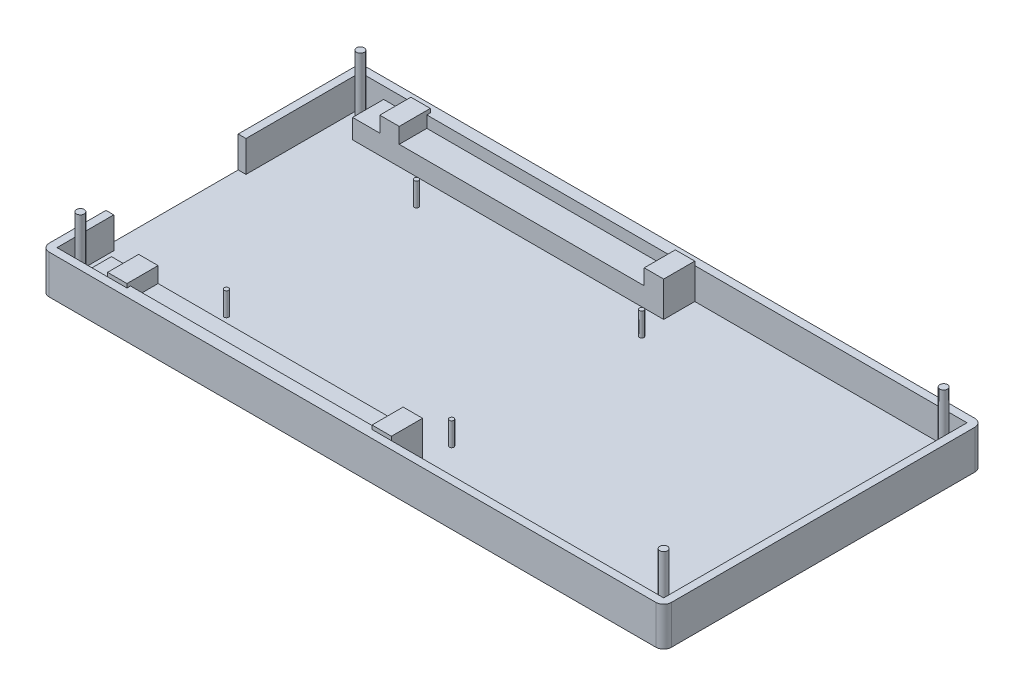
SolidWorks part; units mm, degrees
ref_plane "Front Plane" through (0, 0, 0) normal (0, 0, 1) x (1, 0, 0)
ref_plane "Top Plane" through (0, 0, 0) normal (0, 1, 0) x (1, 0, 0)
ref_plane "Right Plane" through (0, 0, 0) normal (1, 0, 0) x (0, 0, -1)
sketch "Sketch1" plane through (0, 0, 0) normal (0, 1, 0) x (1, 0, 0)
  line L1 (-80, -41) -> (80, -41)
  line L2 (-80, -41) -> (-80, 41)
  line L3 (-80, 41) -> (80, 41)
  line L4 (80, -41) -> (80, 41)
  line L5 (-80, -41) -> (80, 41) construction
  line L6 (-80, 41) -> (80, -41) construction
  point P0 (0, 0)
  dimension "D1" = 160
  dimension "D2" = 82
extrude "Boss-Extrude1" add sketch "Sketch1" along normal blind 10 contours L1 L4 L3 L2
shell "Shell1" thickness 2
sketch "Sketch2" plane through (0, 2, 0) normal (0, 1, 0) x (1, 0, 0)
  line L0 (-78, 39) -> (78, 39) construction
  line L1 (-78, -39) -> (-78, 39) construction
  line L2 (0, 39) -> (0, -41) construction
  line L3 (-78, 39) -> (78, 39) construction
  line L4 (-80, -41) -> (80, -41) construction
  line L5 (-80, 0) -> (80, 0) construction
  line L6 (-80, -41) -> (-80, 41) construction
  line L7 (80, -41) -> (80, 41) construction
  circle A0 centre (-75, 36) radius 1
  circle A1 centre (75, 36) radius 1
  circle A2 centre (75, -36) radius 1
  circle A3 centre (-75, -36) radius 1
  dimension "D1" = 3
  dimension "D2" = 3
  dimension "D3" = 2
extrude "Boss-Extrude2" add sketch "Sketch2" along normal blind 16 contours A0 | A3 | A2 | A1
fillet "Fillet1" radius 2 1 edges at (-80, 5, 41)
fillet "Fillet2" radius 2 1 edges at (-80, 5, -41)
fillet "Fillet3" radius 2 1 edges at (80, 5, -41)
fillet "Fillet4" radius 2 1 edges at (80, 5, 41)
sketch "Sketch7" plane through (0, 2, 0) normal (0, 1, 0) x (1, 0, 0)
  line L0 (-49, 24.45) -> (-49, -24.43)
  line L1 (-78, 39) -> (78, 39) construction
  line L2 (-20.05, 24.45) -> (-20.05, -24.43) construction
  line L3 (-49, 0.01) -> (-52.9634, 0.01) construction
  line L4 (-49, 24.45) -> (8.9, 24.45)
  line L5 (8.9, 24.45) -> (8.9, -24.43)
  line L6 (8.9, -24.43) -> (-49, -24.43)
  line L7 (-78, -39) -> (-78, 39) construction
  circle A0 centre (-49, 24.45) radius 0.575
  circle A1 centre (-49, -24.43) radius 0.575
  circle A2 centre (8.9, -24.43) radius 0.575
  circle A3 centre (8.9, 24.45) radius 0.575
  dimension "D3" = 1.15
  dimension "D1" = 48.88
  dimension "D2" = 14.55
  dimension "D4" = 57.9
  dimension "D5" = 29
extrude "Boss-Extrude3" add sketch "Sketch7" along normal blind 6 contours A2 | A1 | A3 | A0
sketch "Sketch10" plane through (-80, 0, 0) normal (-1, 0, 0) x (0, 0, 1)
  line L0 (24.4, 0) -> (-9.6, 0)
  line L2 (39, 0) -> (-39, 0) construction
  line L3 (-9.6, 0) -> (-9.6, 2)
  line L4 (-9.6, 2) -> (24.4, 2)
  line L5 (-9.6, 2) -> (24.4, 2)
  line L6 (-9.6, 2) -> (-9.6, 10.0297)
  line L7 (24.4, 2) -> (24.4, 10.0297)
  line L8 (-9.6, 10.0297) -> (24.4, 10.0297)
  dimension "D1" = 34
  dimension "D2" = 14.6
  dimension "D3" = 2
extrude "Cut-Extrude1" cut sketch "Sketch10" against normal blind 6 contours L4 L7 L8 L6
sketch "Sketch16" plane through (0, 2, 0) normal (0, 1, 0) x (1, 0, 0)
  line L0 (-49, 24.45) -> (-49, 28.15)
  line L1 (-49, -24.43) -> (-49, -28.13)
  line L2 (8.9, -24.43) -> (8.9, -28.13)
  line L3 (8.9, 24.45) -> (8.9, 28.15)
  line L4 (-78, 39) -> (78, 39) construction
  line L5 (-72, 39) -> (8, 39)
  line L6 (-72, 39) -> (-72, 31)
  line L7 (-72, 31) -> (8, 31)
  line L8 (8, 39) -> (8, 31)
  line L9 (78, 0) -> (-83.4739, 0) construction
  line L10 (78, -39) -> (78, 39) construction
  line L11 (8, -39) -> (8, -31)
  line L12 (-72, -39) -> (8, -39)
  line L13 (-72, -39) -> (-72, -31)
  line L14 (-72, -31) -> (8, -31)
  dimension "D1" = 3.7
  dimension "D2" = 3.7
  dimension "D3" = 8
  dimension "D4" = 80
  dimension "D5" = 6
extrude "Boss-Extrude5" add sketch "Sketch16" along normal blind 5 contours L8 L7 L6 L5 | L14 L11 L12 L13
sketch "Sketch18" plane through (0, 7, 0) normal (0, 1, 0) x (1, 0, 0)
  line L0 (-60, 31) -> (3, 31)
  line L1 (-72, 31) -> (8, 31) construction
  line L2 (-60, 39) -> (-60, 31)
  line L3 (-72, 39) -> (8, 39) construction
  line L4 (-60, 39) -> (-65, 39)
  line L5 (-65, 39) -> (-65, 31)
  line L6 (-72, 31) -> (8, 31) construction
  line L7 (-65, 31) -> (-60, 31)
  line L8 (-28.5, 31) -> (-28.5, 39) construction
  line L9 (8, 31) -> (3, 31)
  line L10 (3, 39) -> (3, 31)
  line L11 (8, 39) -> (8, 31)
  line L12 (3, 39) -> (8, 39)
  line L13 (78, 0) -> (-85.0376, 0) construction
  line L14 (78, -39) -> (78, 39) construction
  line L15 (3, -39) -> (8, -39)
  line L16 (8, -39) -> (8, -31)
  line L17 (8, -31) -> (3, -31)
  line L18 (3, -39) -> (3, -31)
  line L19 (-65, -31) -> (-60, -31)
  line L20 (-65, -39) -> (-65, -31)
  line L21 (-60, -39) -> (-65, -39)
  line L22 (-60, -39) -> (-60, -31)
  dimension "D1" = 63
  dimension "D2" = 5
extrude "Boss-Extrude6" add sketch "Sketch18" along normal blind 4 contours L9 L11 L12 L10 | L7 L5 L4 L2 | L16 L17 L18 L15 | L22 L19 L20 L21
sketch "Sketch21" plane through (0, 0, -39) normal (0, 0, 1) x (1, 0, 0)
  line L1 (-60, 10) -> (3, 10)
  line L2 (-60, 10) -> (-60, 7)
  line L3 (-60, 7) -> (3, 7)
  line L4 (3, 10) -> (3, 7)
extrude "Boss-Extrude7" add sketch "Sketch21" along normal blind 0.9
sketch "Sketch22" plane through (0, 0, 39) normal (0, 0, -1) x (-1, 0, 0)
  line L1 (-3, 10) -> (60, 10)
  line L2 (-3, 10) -> (-3, 7)
  line L3 (-3, 7) -> (60, 7)
  line L4 (60, 10) -> (60, 7)
extrude "Boss-Extrude8" add sketch "Sketch22" along normal blind 0.9
